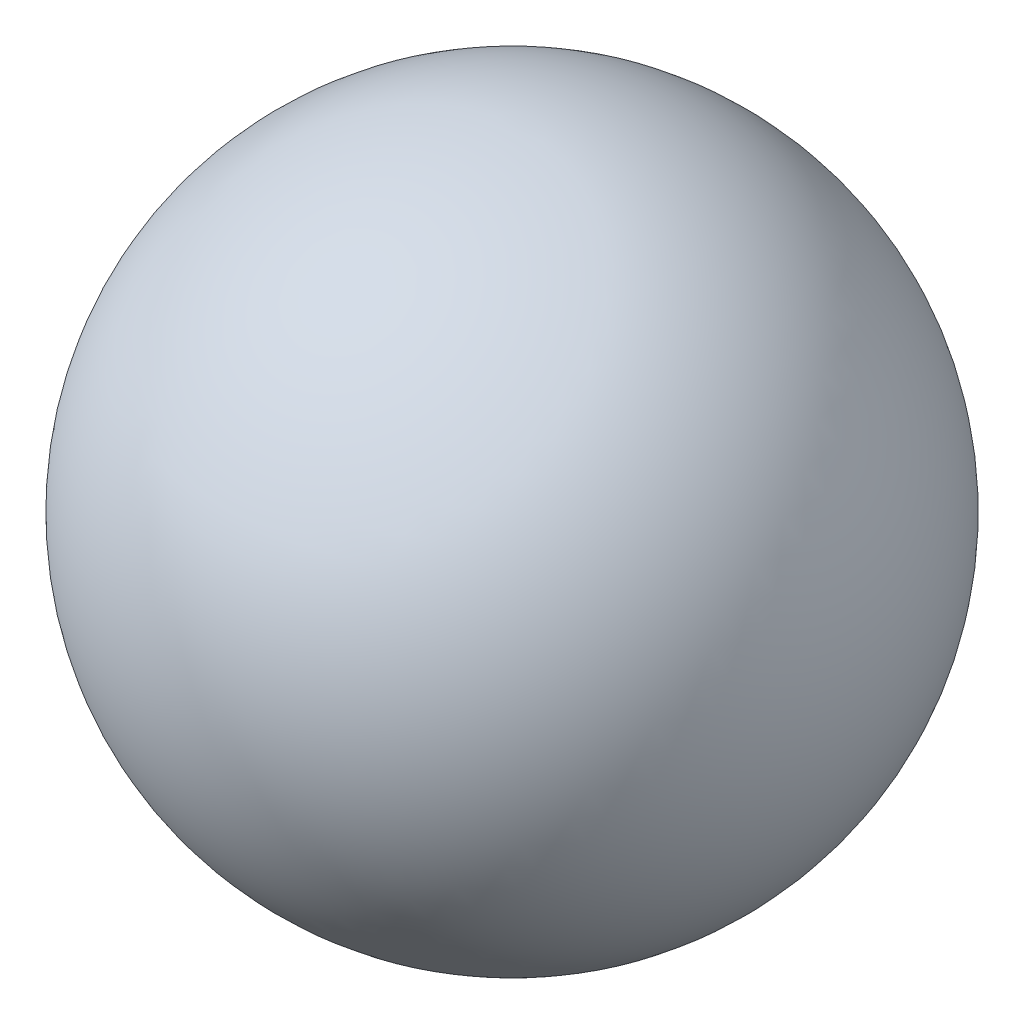
SolidWorks part; units mm, degrees
material "Hexcel AS4C (3000 Filaments)"
ref_plane "Ön Düzlem" through (0, 0, 0) normal (0, 0, 1) x (1, 0, 0)
ref_plane "Üst Düzlem" through (0, 0, 0) normal (0, 1, 0) x (1, 0, 0)
ref_plane "Sağ Düzlem" through (0, 0, 0) normal (1, 0, 0) x (0, 0, -1)
sketch "Çizim1" plane through (0, 0, 0) normal (0, 0, 1) x (1, 0, 0)
  line L0 (0, 32.5) -> (0, -32.5)
  arc A0 (0, 32.5) -> (0, -32.5) centre (0, 0) ccw
  dimension "D1" = 65
revolve "Döndür1" add sketch "Çizim1" angle 360 about L0
